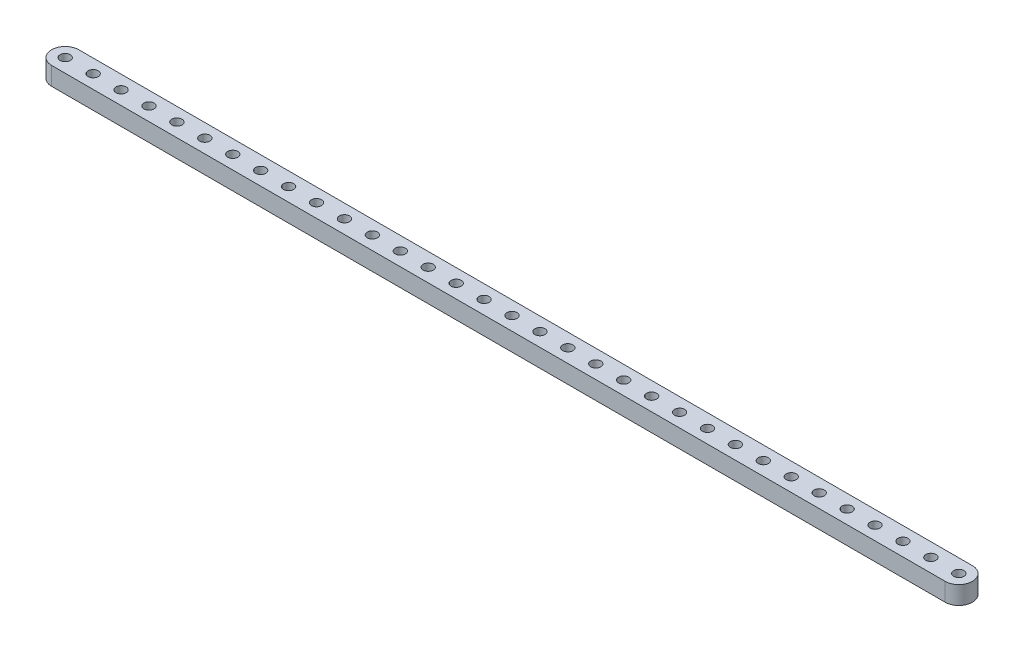
SolidWorks part; units mm, degrees
ref_plane "Front Plane" through (0, 0, 0) normal (0, 0, 1) x (1, 0, 0)
ref_plane "Top Plane" through (0, 0, 0) normal (0, 1, 0) x (1, 0, 0)
ref_plane "Right Plane" through (0, 0, 0) normal (1, 0, 0) x (0, 0, -1)
ref_plane "Plane1" through (0, 6.35, 0) normal (0, 1, 0) x (1, 0, 0)
sketch "Sketch1" plane through (0, 6.35, 0) normal (0, 1, 0) x (1, 0, 0)
  line L0 (156.464, 4.7625) -> (-156.464, 4.7625)
  line L1 (-156.464, -4.7625) -> (156.464, -4.7625)
  arc A0 (156.464, -4.7625) -> (156.464, 4.7625) centre (156.464, 0) ccw
  arc A1 (-156.464, 4.7625) -> (-156.464, -4.7625) centre (-156.464, 0) ccw
  circle A2 centre (156.464, 0) radius 1.778
  circle A3 centre (146.685, 0) radius 1.778
  circle A4 centre (136.906, 0) radius 1.778
  circle A5 centre (127.127, 0) radius 1.778
  circle A6 centre (117.348, 0) radius 1.778
  circle A7 centre (107.569, 0) radius 1.778
  circle A8 centre (97.79, 0) radius 1.778
  circle A9 centre (88.011, 0) radius 1.778
  circle A10 centre (78.232, 0) radius 1.778
  circle A11 centre (68.453, 0) radius 1.778
  circle A12 centre (58.674, 0) radius 1.778
  circle A13 centre (48.895, 0) radius 1.778
  circle A14 centre (39.116, 0) radius 1.778
  circle A15 centre (29.337, 0) radius 1.778
  circle A16 centre (19.558, 0) radius 1.778
  circle A17 centre (9.779, 0) radius 1.778
  circle A18 centre (0, 0) radius 1.778
  circle A19 centre (-9.779, 0) radius 1.778
  circle A20 centre (-19.558, 0) radius 1.778
  circle A21 centre (-29.337, 0) radius 1.778
  circle A22 centre (-39.116, 0) radius 1.778
  circle A23 centre (-48.895, 0) radius 1.778
  circle A24 centre (-58.674, 0) radius 1.778
  circle A25 centre (-68.453, 0) radius 1.778
  circle A26 centre (-78.232, 0) radius 1.778
  circle A27 centre (-88.011, 0) radius 1.778
  circle A28 centre (-97.79, 0) radius 1.778
  circle A29 centre (-107.569, 0) radius 1.778
  circle A30 centre (-117.348, 0) radius 1.778
  circle A31 centre (-127.127, 0) radius 1.778
  circle A32 centre (-136.906, 0) radius 1.778
  circle A33 centre (-146.685, 0) radius 1.778
  circle A34 centre (-156.464, 0) radius 1.778
extrude "Boss-Extrude1" add sketch "Sketch1" against normal blind 6.35
sketch "Sketch2" plane through (0, 6.35, 0) normal (0, 1, 0) x (1, 0, 0)
  line L1 (-161.2265, -14.8384) -> (-73.6032, -14.8384)
  line L2 (-161.2265, -14.8384) -> (-161.2265, 24.3554)
  line L3 (-161.2265, 24.3554) -> (-73.6032, 24.3554)
  line L4 (-73.6032, -14.8384) -> (-73.6032, 24.3554)
